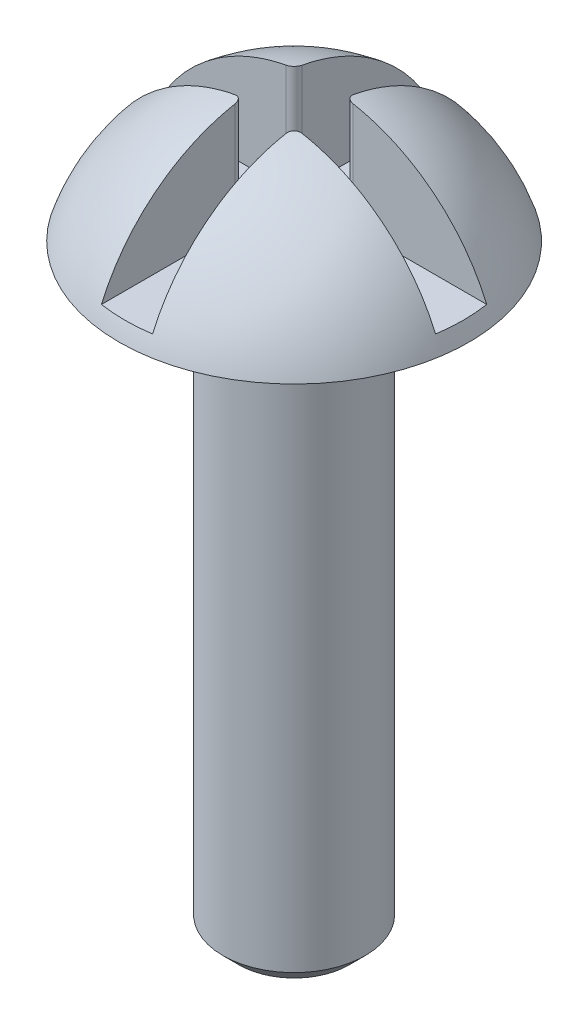
SolidWorks part; units mm, degrees
ref_plane "Front Plane" through (0, 0, 0) normal (0, 0, 1) x (1, 0, 0)
ref_plane "Top Plane" through (0, 0, 0) normal (0, 1, 0) x (1, 0, 0)
ref_plane "Right Plane" through (0, 0, 0) normal (1, 0, 0) x (0, 0, -1)
sketch "Sketch2" plane through (0, 0, 0) normal (1, 0, 0) x (0, 0, -1)
  line L0 (0, 0) -> (2.7813, 0)
  line L1 (0, 0) -> (0, 2.032)
  line L2 (0, 0.4152) -> (0, -1.08) construction
  arc A0 (2.7813, 0) -> (0, 2.032) centre (0, -0.8875) ccw
  dimension "D1" = 2.7813
  dimension "D2" = 2.032
revolve "Revolve1" add sketch "Sketch2" angle 360 about L2
sketch "Sketch3" plane through (0, 0, 0) normal (0, -1, 0) x (1, 0, 0)
  circle A0 centre (0, 0) radius 1.1303
  dimension "D1" = 2.2606
extrude "Boss-Extrude1" add sketch "Sketch3" along normal blind 9.525
chamfer "Chamfer1" distance 0.254 angle 45 1 edges at (0, -9.525, -1.1303)
sketch "Sketch4" plane through (0, 0, 0) normal (0, 1, 0) x (1, 0, 0)
  line L0 (-0.4064, 0.4064) -> (-0.4064, 2.7813)
  line L1 (-0.4064, -2.7813) -> (0.4064, -2.7813)
  line L2 (-0.4064, -2.7813) -> (-0.4064, -0.4064)
  line L3 (-0.4064, 2.7813) -> (0.4064, 2.7813)
  line L4 (0.4064, -2.7813) -> (0.4064, -0.4064)
  line L5 (-0.4064, -2.7813) -> (0.4064, 2.7813) construction
  line L6 (-0.4064, 2.7813) -> (0.4064, -2.7813) construction
  line L7 (2.7813, -0.4064) -> (0.4064, -0.4064)
  line L8 (2.7813, -0.4064) -> (2.7813, 0.4064)
  line L9 (2.7813, 0.4064) -> (0.4064, 0.4064)
  line L10 (-2.7813, -0.4064) -> (-2.7813, 0.4064)
  line L11 (2.7813, -0.4064) -> (-2.7813, 0.4064) construction
  line L12 (2.7813, 0.4064) -> (-2.7813, -0.4064) construction
  line L13 (-0.4064, -0.4064) -> (-2.7813, -0.4064)
  line L15 (0.4064, 0.4064) -> (0.4064, 2.7813)
  line L17 (-0.4064, 0.4064) -> (-2.7813, 0.4064)
  circle A0 centre (0, 0) radius 2.7813 construction
  point P0 (0, 0)
  point P8 (0, 0)
  point P16 (0, 0)
  dimension "D1" = 0.8128
extrude "Cut-Extrude1" cut sketch "Sketch4" along normal through all from offset 0.254
fillet "Fillet1" radius 0.127 4 edges at (0.4064, 1.1144, 0.4064) (0.4064, 1.1144, -0.4064) (-0.4064, 1.1144, 0.4064) (-0.4064, 1.1144, -0.4064)
